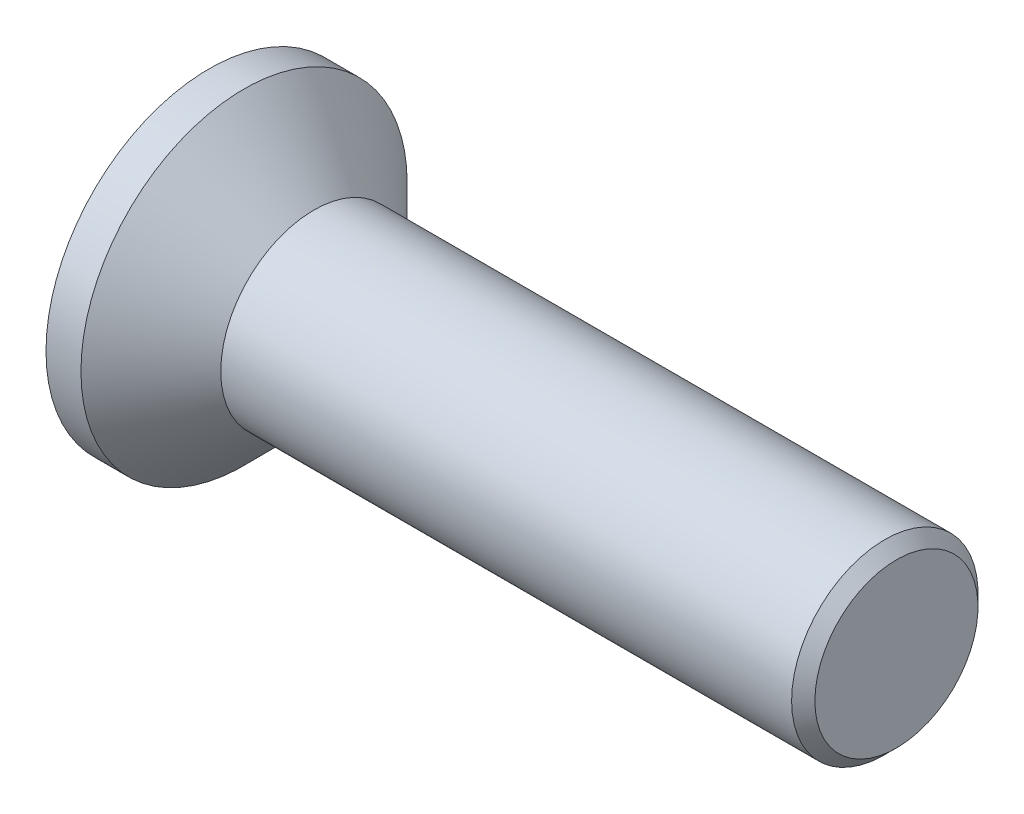
SolidWorks part; units mm, degrees
ref_plane "Front Plane" through (0, 0, 0) normal (0, 0, 1) x (1, 0, 0)
ref_plane "Top Plane" through (0, 0, 0) normal (0, 1, 0) x (1, 0, 0)
ref_plane "Right Plane" through (0, 0, 0) normal (1, 0, 0) x (0, 0, -1)
sketch "Sketch1" plane through (0, 0, 0) normal (0, 0, 1) x (1, 0, 0)
  line L0 (0, 0) -> (29.5, 0)
  line L1 (29.5, 0) -> (29.5, 4)
  line L2 (29.5, 4) -> (4.5, 4)
  line L3 (4.5, 4) -> (1.5, 7)
  line L4 (1.5, 7) -> (0, 7)
  line L5 (0, 7) -> (0, 0)
  dimension "D1" = 4
  dimension "D2" = 45
  dimension "D3" = 4.5
  dimension "D4" = 7
  dimension "D5" = 1.5
  dimension "D6" = 25
revolve "Revolve1" add sketch "Sketch1" angle 360 about L0
cosmetic thread "Cosmetic Thread1" parameters "D1"=24, "D2"=6.619
sketch "Sketch2" plane through (0, 0, 0) normal (-1, 0, 0) x (0, 0, 1)
  line L1 (0, 2.8868) -> (-2.5, 1.4434)
  line L2 (-2.5, 1.4434) -> (-2.5, -1.4434)
  line L3 (-2.5, -1.4434) -> (0, -2.8868)
  line L4 (0, -2.8868) -> (2.5, -1.4434)
  line L5 (2.5, -1.4434) -> (2.5, 1.4434)
  line L6 (2.5, 1.4434) -> (0, 2.8868)
  circle A0 centre (0, 0) radius 2.5 construction
  dimension "D1" = 5
extrude "Cut-Extrude1" cut sketch "Sketch2" against normal blind 3.5
chamfer "Chamfer1" distance 0.5 angle 45 1 edges at (29.5, 0, 4)
equation "\"a\"= 1"
equation "\"b\"= 1"
equation "\"c\"= 1"
equation "\"d\"= 1"
equation "\"e\"= 1"
equation "\"x\"= 1"
equation "\"y\"= 1"
equation "\"z\"= 1"
